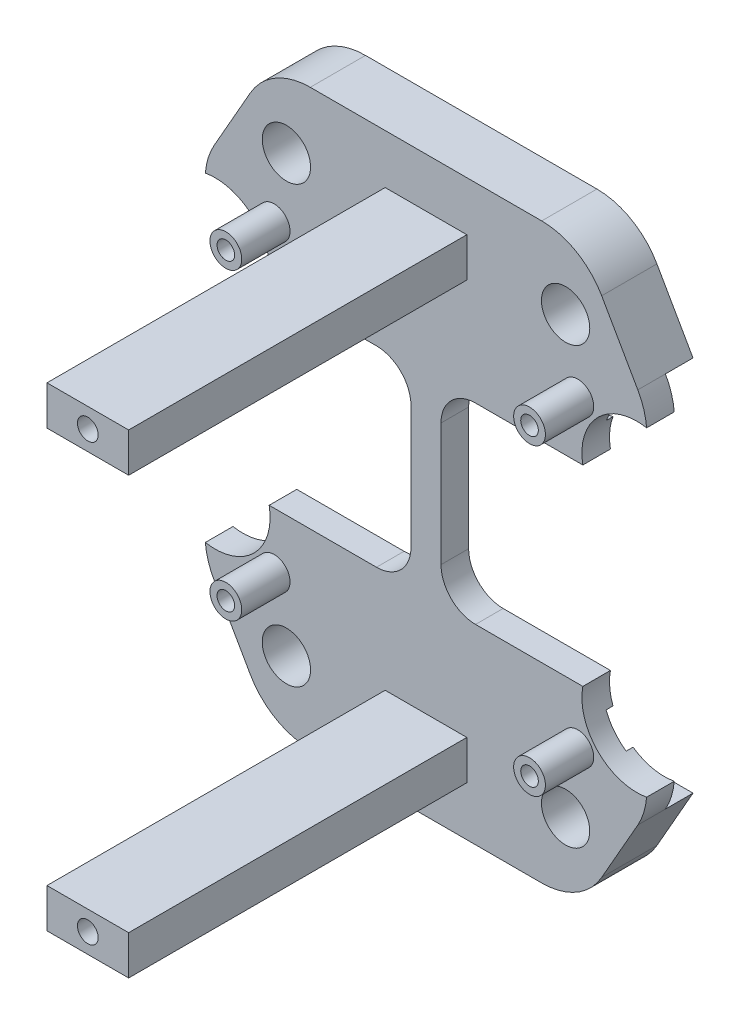
SolidWorks part; units mm, degrees
ref_plane "Ön Düzlem" through (0, 0, 0) normal (0, 0, 1) x (1, 0, 0)
ref_plane "Üst Düzlem" through (0, 0, 0) normal (0, 1, 0) x (1, 0, 0)
ref_plane "Sağ Düzlem" through (0, 0, 0) normal (1, 0, 0) x (0, 0, -1)
sketch "Çizim1" plane through (0, 0, 0) normal (0, 0, 1) x (1, 0, 0)
  line L12 (-26.9423, 14.7698) -> (-7.1182, 14.7698)
  line L13 (-46.9741, 0.8817) -> (-14.6226, 0.8817) construction
  line L14 (-25.3981, 37.3713) -> (-30.6317, 28.1828)
  line L15 (-31.9423, 23.2336) -> (-31.9423, 19.7698)
  line L16 (-26.9423, -13.0064) -> (-7.1182, -13.0064)
  line L17 (0.0577, 32.422) -> (0.0577, 69.5498) construction
  line L18 (-16.7087, 42.422) -> (16.8241, 42.422)
  line L19 (-16.7087, -40.6586) -> (16.8241, -40.6586)
  line L20 (-25.3981, -35.6078) -> (-30.6317, -26.4194)
  line L21 (25.5134, -35.6078) -> (30.747, -26.4194)
  line L22 (32.0577, 23.2336) -> (32.0577, 19.7698)
  line L23 (25.5134, 37.3713) -> (30.747, 28.1828)
  line L24 (27.0577, -13.0064) -> (7.2336, -13.0064)
  line L25 (27.0577, 14.7698) -> (7.2336, 14.7698)
  line L26 (-2.1182, 9.7698) -> (-2.1182, -8.0064)
  line L27 (2.2336, 9.7698) -> (2.2336, -8.0064)
  line L28 (32.0577, -18.0064) -> (32.0577, -21.4701)
  line L29 (-31.9423, -18.0064) -> (-31.9423, -21.4701)
  circle A0 centre (20.2843, 32.422) radius 1.5
  circle A1 centre (-20.1689, 32.422) radius 1.5
  circle A2 centre (-20.1689, -30.6586) radius 1.5
  circle A3 centre (20.2843, -30.6586) radius 1.5
  circle A16 centre (22.0577, -21.1183) radius 1.275
  circle A17 centre (-21.9423, -21.1183) radius 1.275
  circle A18 centre (22.0577, 22.8817) radius 1.275
  circle A19 centre (-21.9423, 22.8817) radius 1.275
  arc A20 (-30.6317, 28.1828) -> (-31.9423, 23.2336) centre (-21.9423, 23.2336) ccw
  arc A21 (-25.3981, 37.3713) -> (-16.7087, 42.422) centre (-16.7087, 32.422) cw
  arc A22 (-25.3981, -35.6078) -> (-16.7087, -40.6586) centre (-16.7087, -30.6586) ccw
  arc A23 (-30.6317, -26.4194) -> (-31.9423, -21.4701) centre (-21.9423, -21.4701) cw
  arc A24 (30.747, -26.4194) -> (32.0577, -21.4701) centre (22.0577, -21.4701) ccw
  arc A25 (25.5134, -35.6078) -> (16.8241, -40.6586) centre (16.8241, -30.6586) cw
  arc A26 (25.5134, 37.3713) -> (16.8241, 42.422) centre (16.8241, 32.422) ccw
  arc A27 (30.747, 28.1828) -> (32.0577, 23.2336) centre (22.0577, 23.2336) cw
  arc A28 (32.0577, -18.0064) -> (27.0577, -13.0064) centre (27.0577, -18.0064) ccw
  arc A29 (-26.9423, -13.0064) -> (-31.9423, -18.0064) centre (-26.9423, -18.0064) ccw
  arc A30 (7.2336, -13.0064) -> (2.2336, -8.0064) centre (7.2336, -8.0064) cw
  arc A31 (-2.1182, -8.0064) -> (-7.1182, -13.0064) centre (-7.1182, -8.0064) cw
  arc A32 (27.0577, 14.7698) -> (32.0577, 19.7698) centre (27.0577, 19.7698) ccw
  arc A33 (7.2336, 14.7698) -> (2.2336, 9.7698) centre (7.2336, 9.7698) ccw
  arc A34 (-7.1182, 14.7698) -> (-2.1182, 9.7698) centre (-7.1182, 9.7698) cw
  arc A35 (-31.9423, 19.7698) -> (-26.9423, 14.7698) centre (-26.9423, 19.7698) ccw
  circle A36 centre (0.0577, 32.422) radius 1.5
  circle A37 centre (0.0577, -30.6586) radius 1.5
  point P16 (32.0577, 0.8817)
  point P26 (0.0577, 42.422)
  point P27 (-31.9423, 0.8817)
  point P40 (0.0577, -40.6586)
  point P53 (32.0577, -13.0064)
  point P56 (-31.9423, -13.0064)
  point P64 (2.2336, -13.0064)
  point P67 (-2.1182, -13.0064)
  point P70 (32.0577, 14.7698)
  point P73 (2.2336, 14.7698)
  point P76 (-2.1182, 14.7698)
  point P79 (-31.9423, 14.7698)
  dimension "D1" = 10
  dimension "D2" = 5
extrude "Yükseklik-Ekstrüzyon1" add sketch "Çizim1" along normal blind 8
sketch "Çizim2" plane through (0, 0, 0) normal (0, 0, -1) x (-1, 0, 0)
  circle A0 centre (-22.0577, 22.8817) radius 4
  circle A1 centre (21.9423, 22.8817) radius 4
  circle A2 centre (-22.0577, -21.1183) radius 4
  circle A3 centre (21.9423, -21.1183) radius 4
  circle A4 centre (-0.0577, 32.422) radius 4
  circle A5 centre (-0.0577, -30.6586) radius 4
  dimension "D1" = 8
extrude "Kes-Ekstrüzyon1" cut sketch "Çizim2" against normal blind 5
sketch "Çizim3" plane through (0, 0, 8) normal (0, 0, 1) x (1, 0, 0)
  circle A0 centre (-20.1689, 32.422) radius 3.5
  circle A1 centre (20.2843, 32.422) radius 3.5
  circle A2 centre (20.2843, -30.6586) radius 3.5
  circle A3 centre (-20.1689, -30.6586) radius 3.5
  dimension "D1" = 7
extrude "Kes-Ekstrüzyon2" cut sketch "Çizim3" against normal blind 5
sketch "Çizim5" plane through (0, 0, 8) normal (0, 0, 1) x (1, 0, 0)
  line L0 (-2.1182, 0.8817) -> (-29.4082, 0.8817) construction
  line L1 (-5.8592, 35.2656) -> (5.9745, 35.2656)
  line L2 (-5.8592, 35.2656) -> (-5.8592, 29.5785)
  line L3 (-5.8592, 29.5785) -> (5.9745, 29.5785)
  line L4 (5.9745, 35.2656) -> (5.9745, 29.5785)
  line L5 (-5.8592, 35.2656) -> (5.9745, 29.5785) construction
  line L6 (-5.8592, 29.5785) -> (5.9745, 35.2656) construction
  line L7 (-2.1182, 9.7698) -> (-2.1182, -8.0064) construction
  line L8 (-5.8592, -27.815) -> (5.9745, -33.5021) construction
  line L9 (-5.8592, -33.5021) -> (5.9745, -27.815) construction
  line L10 (5.9745, -33.5021) -> (5.9745, -27.815)
  line L11 (-5.8592, -27.815) -> (5.9745, -27.815)
  line L12 (-5.8592, -33.5021) -> (-5.8592, -27.815)
  line L13 (-5.8592, -33.5021) -> (5.9745, -33.5021)
  point P0 (0.0577, 32.422)
  point P14 (0.0577, -30.6586)
extrude "Yükseklik-Ekstrüzyon2" add sketch "Çizim5" along normal blind 49
sketch "Çizim6" plane through (0, 0, 8) normal (0, 0, -1) x (-1, 0, 0)
  circle A0 centre (-0.0577, 32.422) radius 1.5 construction
  circle A1 centre (-0.0577, -30.6586) radius 1.5
  circle A2 centre (-0.0577, -30.6586) radius 1.5
  circle A3 centre (-0.0577, 32.422) radius 1.5
  dimension "D1" = 0
extrude "Kes-Ekstrüzyon3" cut sketch "Çizim6" against normal blind 70
sketch "Çizim7" plane through (0, 0, 8) normal (0, 0, 1) x (1, 0, 0)
  line L0 (2.2336, 0.8817) -> (22.6453, 0.8817) construction
  line L1 (2.2336, -8.0064) -> (2.2336, 9.7698) construction
  line L2 (22.6453, 0.8817) -> (0.0577, 42.422) construction
  line L3 (16.8241, 42.422) -> (-16.7087, 42.422) construction
  line L4 (0.0577, 42.422) -> (0.0577, 53.5335) construction
  circle A0 centre (30.5932, 16.2343) radius 7.9479
  arc A1 (27.0577, 14.7698) -> (32.0577, 19.7698) centre (27.0577, 19.7698) ccw construction
  circle A2 centre (-30.4779, 16.2343) radius 7.9479
  circle A3 centre (30.5932, -14.4708) radius 7.9479
  circle A4 centre (-30.4779, -14.4708) radius 7.9479
extrude "Kes-Ekstrüzyon4" cut sketch "Çizim7" against normal mid plane 189
sketch "Çizim8" plane through (0, 0, 8) normal (0, 0, 1) x (1, 0, 0)
  circle A0 centre (-21.9423, -21.1183) radius 1.275
  circle A1 centre (22.0577, -21.1183) radius 1.275
  circle A2 centre (22.0577, 22.8817) radius 1.275
  circle A3 centre (-21.9423, 22.8817) radius 1.275
  circle A4 centre (-21.9423, 22.8817) radius 2.3031
  circle A5 centre (22.0577, 22.8817) radius 2.3031
  circle A6 centre (-21.9423, -21.1183) radius 2.3031
  circle A7 centre (22.0577, -21.1183) radius 2.3031
extrude "Yükseklik-Ekstrüzyon3" add sketch "Çizim8" along normal blind 7
sketch "Çizim9" plane through (2.2336, 0, 0) normal (1, 0, 0) x (0, 0, -1)
  line L0 (-8, 28.1828) -> (0, 28.1828) construction
  line L1 (-4, 28.1828) -> (5.1845, 28.1828)
  line L2 (-4, 28.1828) -> (-4, -26.4194)
  line L3 (-4, -26.4194) -> (5.1845, -26.4194)
  line L4 (5.1845, 28.1828) -> (5.1845, -26.4194)
extrude "Kes-Ekstrüzyon5" cut sketch "Çizim9" against normal mid plane 98
